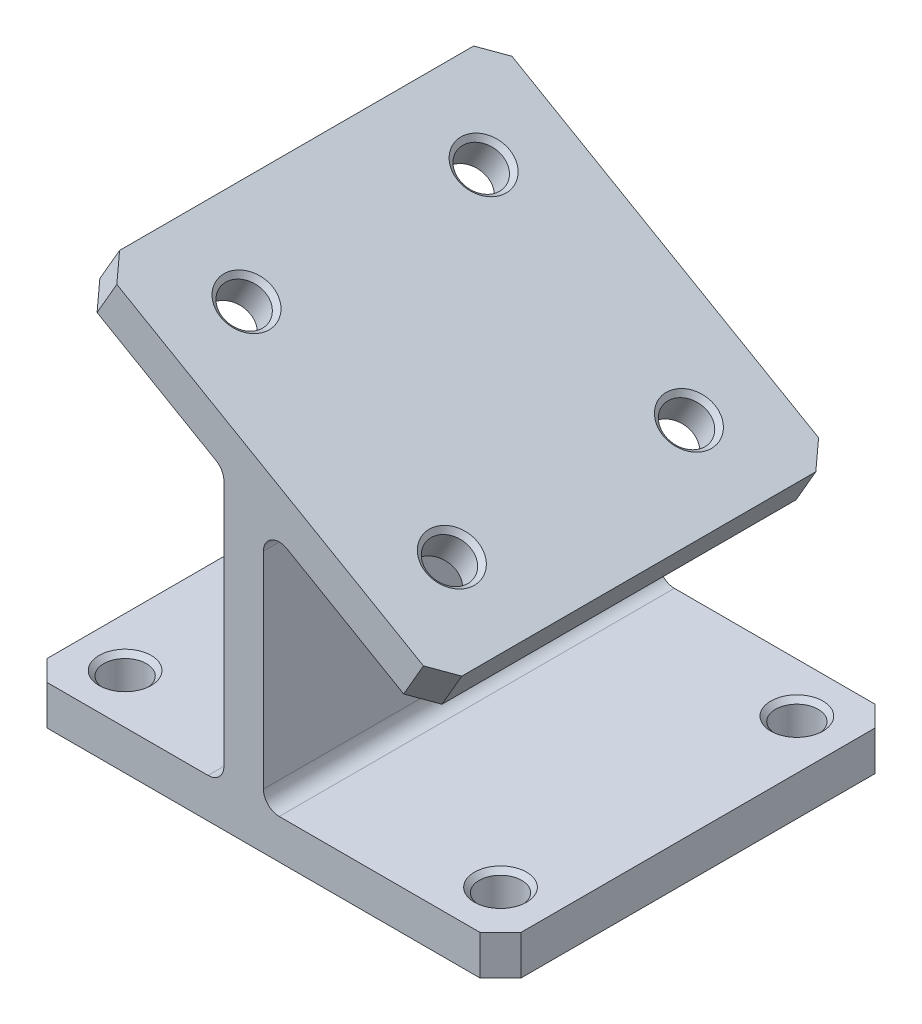
SolidWorks part; units mm, degrees
material "1060 Alloy"
ref_plane "Front Plane" through (0, 0, 0) normal (0, 0, 1) x (1, 0, 0)
ref_plane "Top Plane" through (0, 0, 0) normal (0, 1, 0) x (1, 0, 0)
ref_plane "Right Plane" through (0, 0, 0) normal (1, 0, 0) x (0, 0, -1)
sketch "Sketch1" plane through (0, 0, 0) normal (0, 0, 1) x (1, 0, 0)
  line L0 (0, 2.54) -> (0, 42.2644)
  line L1 (-1.27, 44.4641) -> (-23.2426, 57.15)
  line L2 (-23.2426, 57.15) -> (-20.0676, 62.6493)
  line L3 (-20.0676, 62.6493) -> (34.925, 30.8993)
  line L4 (34.925, 30.8993) -> (31.75, 25.4)
  line L5 (31.75, 25.4) -> (10.16, 37.865)
  line L6 (6.35, 35.6653) -> (6.35, 2.54)
  line L7 (8.89, 0) -> (44.45, 0)
  line L8 (44.45, 0) -> (44.45, -6.35)
  line L9 (44.45, -6.35) -> (-31.75, -6.35)
  line L10 (-31.75, -6.35) -> (-31.75, 0)
  line L11 (-31.75, 0) -> (-2.54, 0)
  arc A0 (6.35, 2.54) -> (8.89, 0) centre (8.89, 2.54) ccw
  arc A1 (0, 2.54) -> (-2.54, 0) centre (-2.54, 2.54) cw
  arc A2 (10.16, 37.865) -> (6.35, 35.6653) centre (8.89, 35.6653) ccw
  arc A3 (0, 42.2644) -> (-1.27, 44.4641) centre (-2.54, 42.2644) ccw
  point P18 (0, 0)
  dimension "D10" = 2.54
  dimension "D1" = 76.2
  dimension "D2" = 31.75
  dimension "D3" = 6.35
  dimension "D4" = 6.35
  dimension "D5" = 31.75
  dimension "D6" = 30
  dimension "D7" = 6.35
  dimension "D8" = 63.5
  dimension "D9" = 63.5
extrude "Boss-Extrude1" add sketch "Sketch1" along normal mid plane 63.5
chamfer "Chamfer1" distance 3.302 angle 45 8 edges at (-31.75, -3.175, 31.75) (-31.75, -3.175, -31.75) (44.45, -3.175, -31.75) (44.45, -3.175, 31.75) (33.3375, 28.1496, -31.75) (-21.6551, 59.8996, -31.75) (-21.6551, 59.8996, 31.75) (33.3375, 28.1496, 31.75)
sketch "Sketch2" plane through (22.111, 38.2974, 0) normal (0.5, 0.866, 0) x (0.866, -0.5, 0)
  line L0 (-48.7037, -28.448) -> (-48.7037, 28.448) construction
  line L1 (-36.0037, 19.05) -> (2.0963, 19.05) construction
  line L2 (-36.0037, 19.05) -> (-36.0037, -19.05) construction
  line L3 (-36.0037, -19.05) -> (2.0963, -19.05) construction
  line L4 (2.0963, 19.05) -> (2.0963, -19.05) construction
  line L5 (-36.0037, 19.05) -> (2.0963, -19.05) construction
  line L6 (-36.0037, -19.05) -> (2.0963, 19.05) construction
  line L7 (11.4943, -31.75) -> (-45.4017, -31.75) construction
  circle A0 centre (-36.0037, 19.05) radius 3.429
  circle A1 centre (2.0963, 19.05) radius 3.429
  circle A2 centre (-36.0037, -19.05) radius 3.429
  circle A3 centre (2.0963, -19.05) radius 3.429
  point P0 (-16.9537, 0)
  dimension "D5" = 6.858
  dimension "D1" = 38.1
  dimension "D2" = 38.1
  dimension "D3" = 31.75
  dimension "D4" = 31.75
extrude "Cut-Extrude1" cut sketch "Sketch2" against normal up to next
sketch "Sketch3" plane through (0, -6.35, 0) normal (0, -1, 0) x (1, 0, 0)
  line L1 (-23.8125, 23.8125) -> (36.5125, 23.8125) construction
  line L2 (-23.8125, 23.8125) -> (-23.8125, -23.8125) construction
  line L3 (-23.8125, -23.8125) -> (36.5125, -23.8125) construction
  line L4 (36.5125, 23.8125) -> (36.5125, -23.8125) construction
  line L5 (-23.8125, 23.8125) -> (36.5125, -23.8125) construction
  line L6 (-23.8125, -23.8125) -> (36.5125, 23.8125) construction
  line L7 (44.45, 28.448) -> (44.45, -28.448) construction
  circle A0 centre (-23.8125, 23.8125) radius 3.429
  circle A1 centre (36.5125, 23.8125) radius 3.429
  circle A2 centre (-23.8125, -23.8125) radius 3.429
  circle A3 centre (36.5125, -23.8125) radius 3.429
  point P0 (6.35, 0)
  point P7 (44.45, 0)
  dimension "D3" = 6.858
  dimension "D1" = 47.625
  dimension "D2" = 60.325
extrude "Cut-Extrude2" cut sketch "Sketch3" against normal up to next
chamfer "Chamfer2" distance 0.762 angle 45 16 edges at (-23.8125, 0, -27.2415) (-20.3835, -6.35, -23.8125) (-23.8125, 0, 20.3835) (-20.3835, -6.35, 23.8125) (39.9415, 0, -23.8125) (39.9415, -6.35, -23.8125) (39.9415, 0, 23.8125) (39.9415, -6.35, 23.8125) (17.7819, 33.4645, -19.05) (20.9569, 38.9638, -19.05) (17.7819, 33.4645, 19.05) (20.9569, 38.9638, 19.05) (-15.2137, 52.5145, -19.05) (-12.0387, 58.0138, -19.05) (-15.2137, 52.5145, 19.05) (-12.0387, 58.0138, 19.05)
